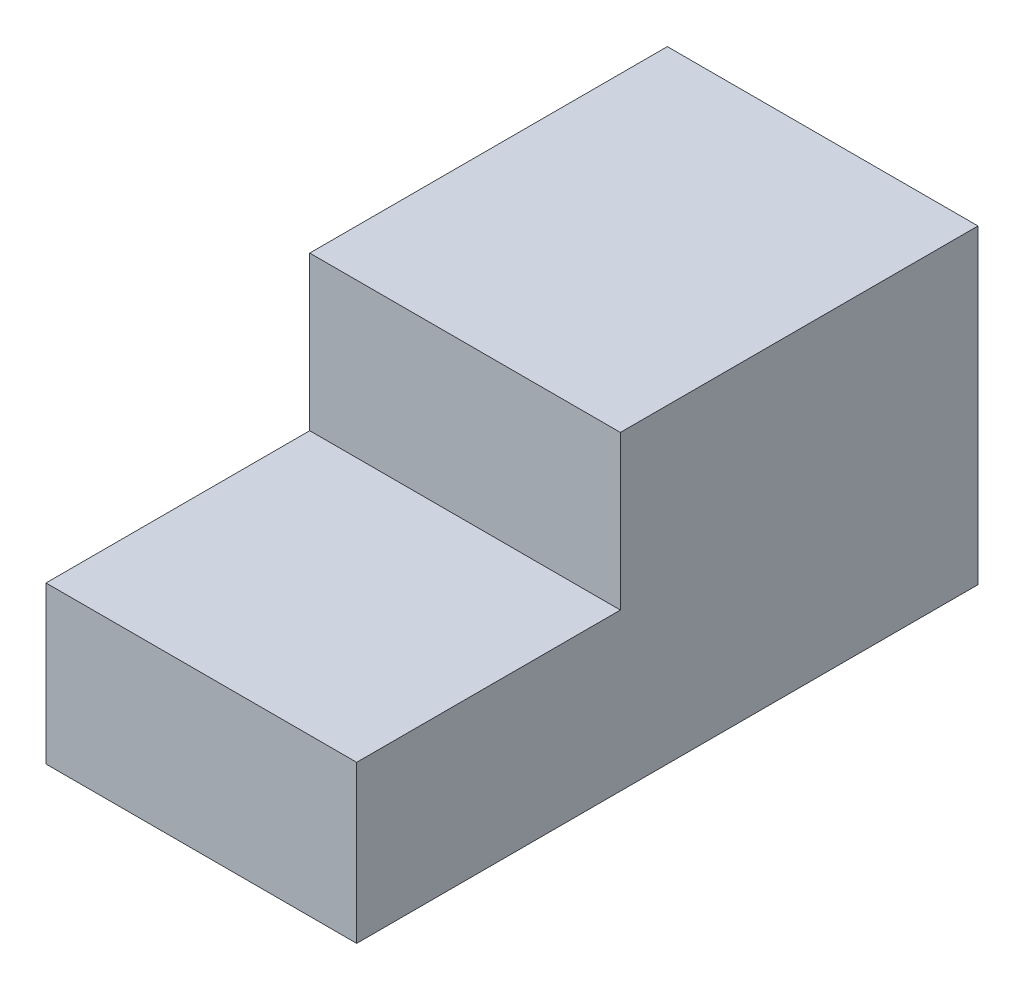
SolidWorks part; units mm, degrees
ref_plane "Front Plane" through (0, 0, 0) normal (0, 0, 1) x (1, 0, 0)
ref_plane "Top Plane" through (0, 0, 0) normal (0, 1, 0) x (1, 0, 0)
ref_plane "Right Plane" through (0, 0, 0) normal (1, 0, 0) x (0, 0, -1)
sketch "Sketch1" plane through (0, 0, 0) normal (1, 0, 0) x (0, 0, -1)
  line L1 (-1000, -252.4116) -> (1000, -252.4116)
  line L2 (-1000, -252.4116) -> (-1000, 252.4116)
  line L3 (-1000, 252.4116) -> (1000, 252.4116)
  line L4 (1000, -252.4116) -> (1000, 252.4116)
  line L5 (-1000, -252.4116) -> (1000, 252.4116) construction
  line L6 (-1000, 252.4116) -> (1000, -252.4116) construction
  line L7 (-151.1254, 252.4116) -> (1000, 252.4116)
  line L8 (-151.1254, 252.4116) -> (-151.1254, 747.5884)
  line L9 (-151.1254, 747.5884) -> (1000, 747.5884)
  line L10 (1000, 252.4116) -> (1000, 747.5884)
  point P0 (0, 0)
  dimension "D1" = 2000
  dimension "D2" = 1000
extrude "Boss-Extrude1" add sketch "Sketch1" along normal mid plane 1000 contours L1 L4 L3 L2 | L3 L10 L9 L8
